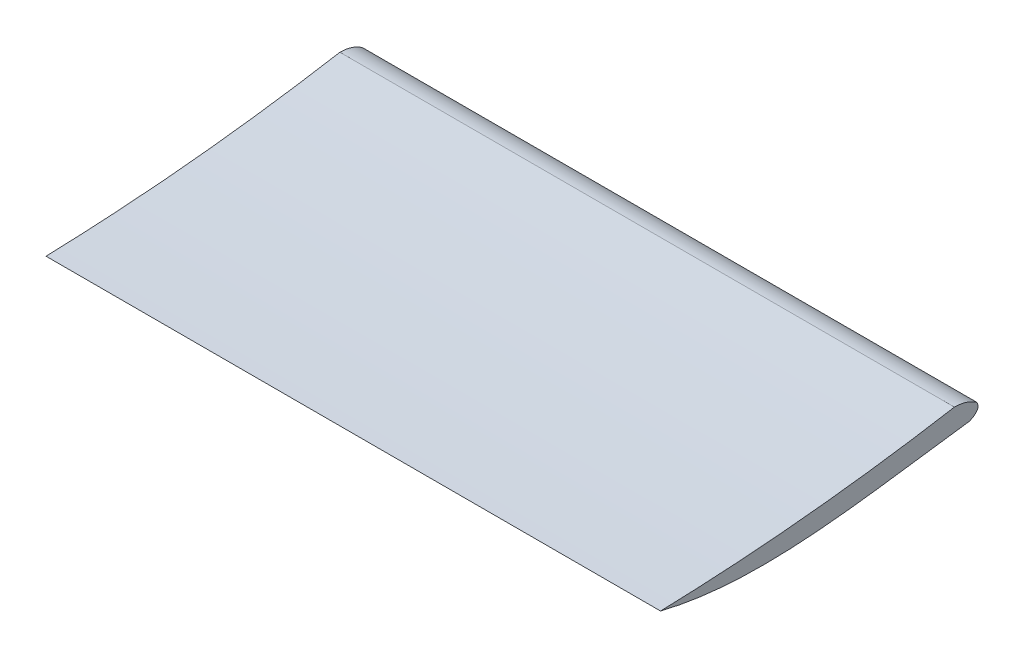
SolidWorks part; units mm, degrees
material "Thornel VCB-20 Carbon Cloth"
ref_plane "Front Plane" through (0, 0, 0) normal (0, 0, 1) x (1, 0, 0)
ref_plane "Top Plane" through (0, 0, 0) normal (0, 1, 0) x (1, 0, 0)
ref_plane "Right Plane" through (0, 0, 0) normal (1, 0, 0) x (0, 0, -1)
sketch "Sketch2" plane through (0, 0, 0) normal (1, 0, 0) x (0, 0.0175, -0.9998)
  spline S0 degree 2 poles (0, 0) (-3.2638, 2.3728) (-7.3904, 2.489) knots 0 0 0 1 1 1
  spline S1 degree 3 poles (-2.5325, -4.1414) (-36.3617, -7.817) (-70.8253, -14.6146) (-104.7078, -5.6353) knots 0 0 0 0 1 1 1 1
  spline S2 degree 2 poles (-104.7078, -5.6353) (-55.7897, -5.0192) (-7.3904, 2.489) knots 0 0 0 1 1 1
  spline S3 degree 2 poles (-2.5325, -4.1414) (1.3412, -2.5988) (0, 0) knots 0 0 0 1 1 1
  point P4 (0, 0)
  point P6 (-89.7696, -12.0637)
  point P7 (-144.5134, 0)
  point P8 (-10.0926, -6.1969)
  point P9 (-3.8059, -1.892)
  point P10 (0, 0)
  point P11 (-3.8059, 4.0504)
  point P12 (0, -1.892)
  point P13 (-1.671, -3.5917)
  point P14 (-22.3266, 6.2398)
  point P15 (-49.7598, -12.2585)
  point P16 (-0.5706, -0.8468)
  point P17 (-1.6768, -1.892)
  point P18 (0.32, -0.9399)
  point P19 (-1.3754, -2.5009)
  point P20 (-6.842, 4.3445)
  point P21 (-144.4916, -1.9646)
  point P22 (-12.9273, 4.6675)
  point P23 (-37.7898, -8.2914)
  point P24 (-119.0162, -1.2519)
  point P25 (-62.2908, -10.0132)
  point P26 (0, 0)
  point P28 (-67.1486, -4.1414)
  point P30 (-104.7078, -5.6353)
  point P33 (-2.5325, -4.1414)
  point P34 (-3.74, 1.2407)
  point P35 (-7.3904, 2.489)
  point P36 (-2.5325, 1.4466)
extrude "Boss-Extrude1" add sketch "Sketch2" along normal blind 203.2
sketch "Sketch3" plane through (0, 0, 0) normal (-1, 0, 0) x (0, 0, 1)
  line L1 (75.4592, -3.7063) -> (95.4592, -3.7063)
  line L2 (75.4592, -3.7063) -> (75.4592, -8.7063)
  line L3 (75.4592, -8.7063) -> (95.4592, -8.7063)
  line L4 (95.4592, -3.7063) -> (95.4592, -8.7063)
  line L5 (75.4592, -3.7063) -> (95.4592, -8.7063) construction
  line L6 (75.4592, -8.7063) -> (95.4592, -3.7063) construction
  point P0 (85.4592, -6.2063)
  dimension "D1" = 20
  dimension "D2" = 5
